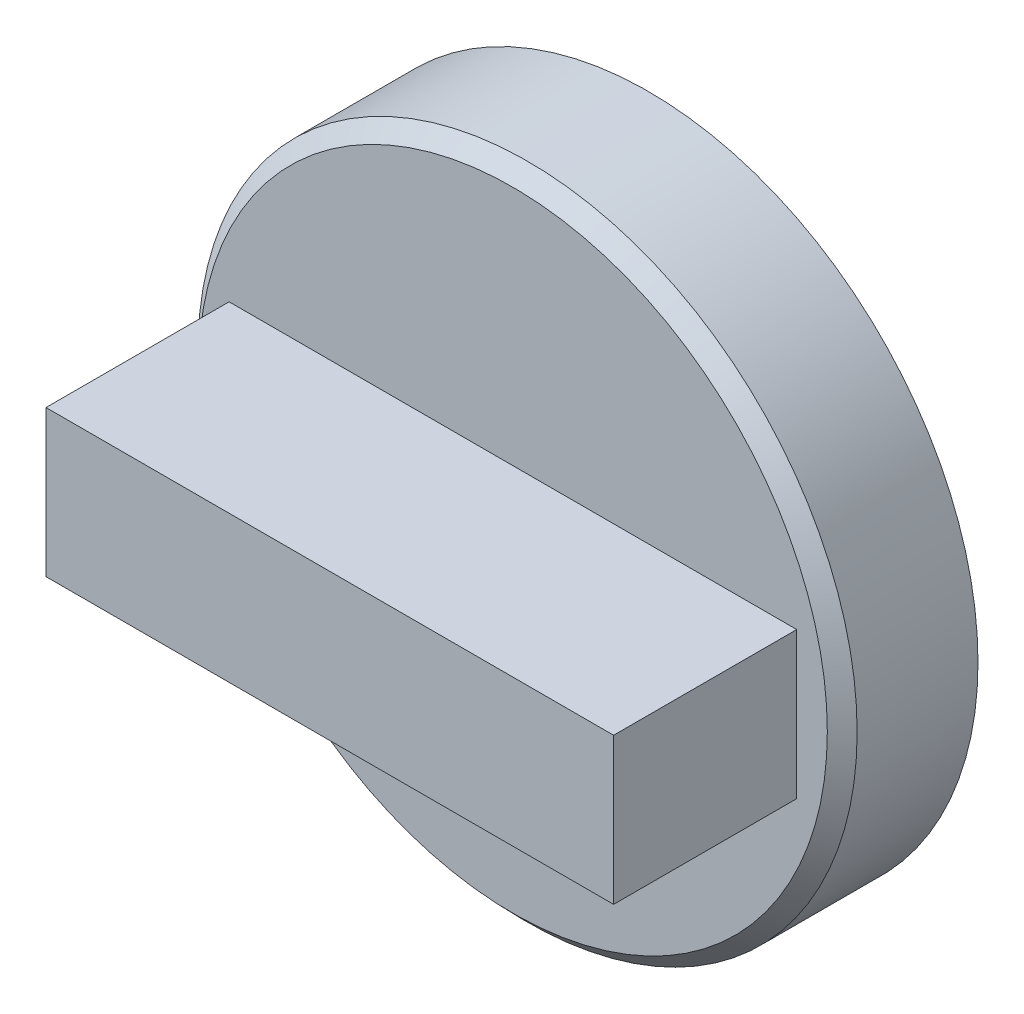
SolidWorks part; units mm, degrees
ref_plane "Front Plane" through (0, 0, 0) normal (0, 0, 1) x (1, 0, 0)
ref_plane "Top Plane" through (0, 0, 0) normal (0, 1, 0) x (1, 0, 0)
ref_plane "Right Plane" through (0, 0, 0) normal (1, 0, 0) x (0, 0, -1)
sketch "Sketch3" plane through (0, 0, 0) normal (0, 0, 1) x (1, 0, 0)
  circle A0 centre (0, 0) radius 90
  dimension "D1" = 180
extrude "Boss-Extrude1" add sketch "Sketch3" along normal blind 37
chamfer "Chamfer1" distance 4 angle 46 1 edges at (90, 0, 37)
sketch "Sketch4" plane through (0, 0, 37) normal (0, 0, 1) x (1, 0, 0)
  line L1 (-77.5, 20) -> (77.5, 20)
  line L2 (-77.5, 20) -> (-77.5, -20)
  line L3 (-77.5, -20) -> (77.5, -20)
  line L4 (77.5, 20) -> (77.5, -20)
  line L5 (-77.5, 20) -> (77.5, -20) construction
  line L6 (-77.5, -20) -> (77.5, 20) construction
  point P0 (0, 0)
  dimension "D1" = 155
  dimension "D2" = 40
extrude "Boss-Extrude2" add sketch "Sketch4" along normal blind 50
